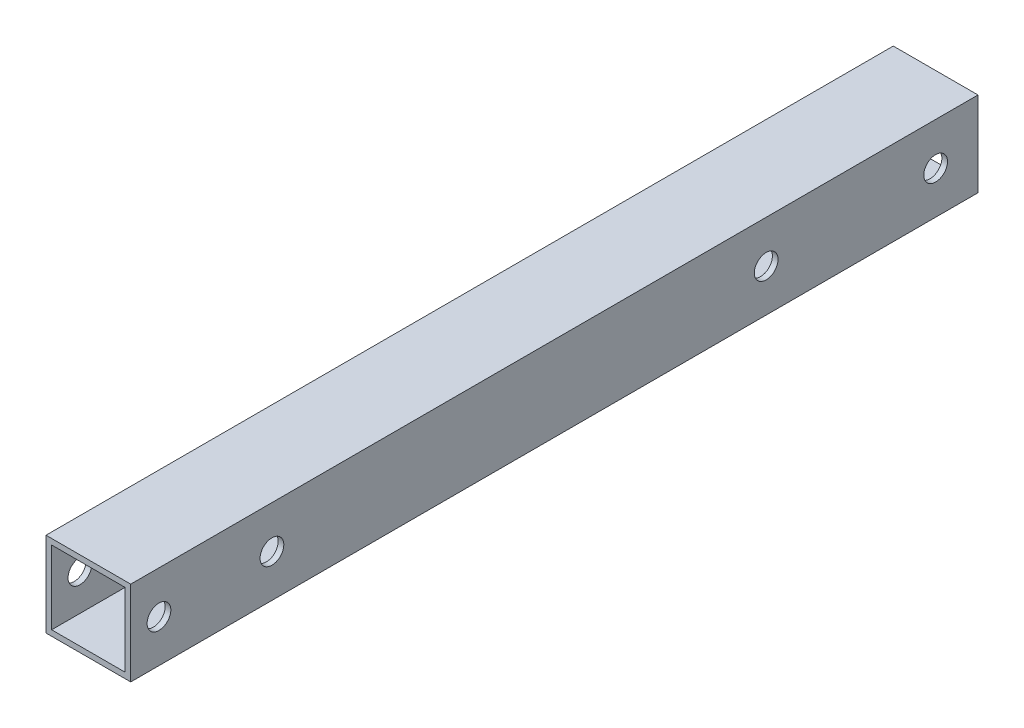
SolidWorks part; units mm, degrees
material "1060 合金"
ref_plane "正面" through (0, 0, 0) normal (0, 0, 1) x (1, 0, 0)
ref_plane "平面" through (0, 0, 0) normal (0, 1, 0) x (1, 0, 0)
ref_plane "右側面" through (0, 0, 0) normal (1, 0, 0) x (0, 0, -1)
sketch "ｽｹｯﾁ1" plane through (0, 0, 0) normal (0, 0, 1) x (1, 0, 0)
  line L1 (7.5, 7.5) -> (-7.5, 7.5)
  line L2 (7.5, 7.5) -> (7.5, -7.5)
  line L3 (7.5, -7.5) -> (-7.5, -7.5)
  line L4 (-7.5, 7.5) -> (-7.5, -7.5)
  line L5 (7.5, 7.5) -> (-7.5, -7.5) construction
  line L6 (7.5, -7.5) -> (-7.5, 7.5) construction
  point P0 (0, 0)
  dimension "D1" = 15
extrude "押し出し-薄板1" add sketch "ｽｹｯﾁ1" along normal blind 150 thin thin type one direction reverse wall 1
sketch "ｽｹｯﾁ2" plane through (7.5, 0, 0) normal (1, 0, 0) x (0, 0, -1)
  line L0 (-150, 0) -> (0, 0) construction
  line L1 (-150, -7.5) -> (-150, 7.5) construction
  line L2 (0, 0) -> (-75, 0) construction
  line L3 (-75, 0) -> (-75, 7.5) construction
  line L4 (-150, 7.5) -> (0, 7.5) construction
  line L5 (0, -7.5) -> (0, 7.5) construction
  circle A0 centre (-7.5, 0) radius 2.1
  circle A1 centre (-37.5, 0) radius 2.1
  dimension "D1" = 30
  dimension "D2" = 7.5
  dimension "D3" = 4.2
extrude "ｶｯﾄ - 押し出し1" cut sketch "ｽｹｯﾁ2" against normal through all
sketch "ｽｹｯﾁ4" plane through (7.5, 0, 0) normal (1, 0, 0) x (0, 0, -1)
  line L0 (-150, 0) -> (0, 0) construction
  line L1 (-150, -7.5) -> (-150, 7.5) construction
  circle A0 centre (-145, 0) radius 2.1
  circle A1 centre (-125, 0) radius 2.1
  dimension "D1" = 5
  dimension "D2" = 20
  dimension "D3" = 4.2
extrude "ｶｯﾄ - 押し出し3" cut sketch "ｽｹｯﾁ4" against normal through all
